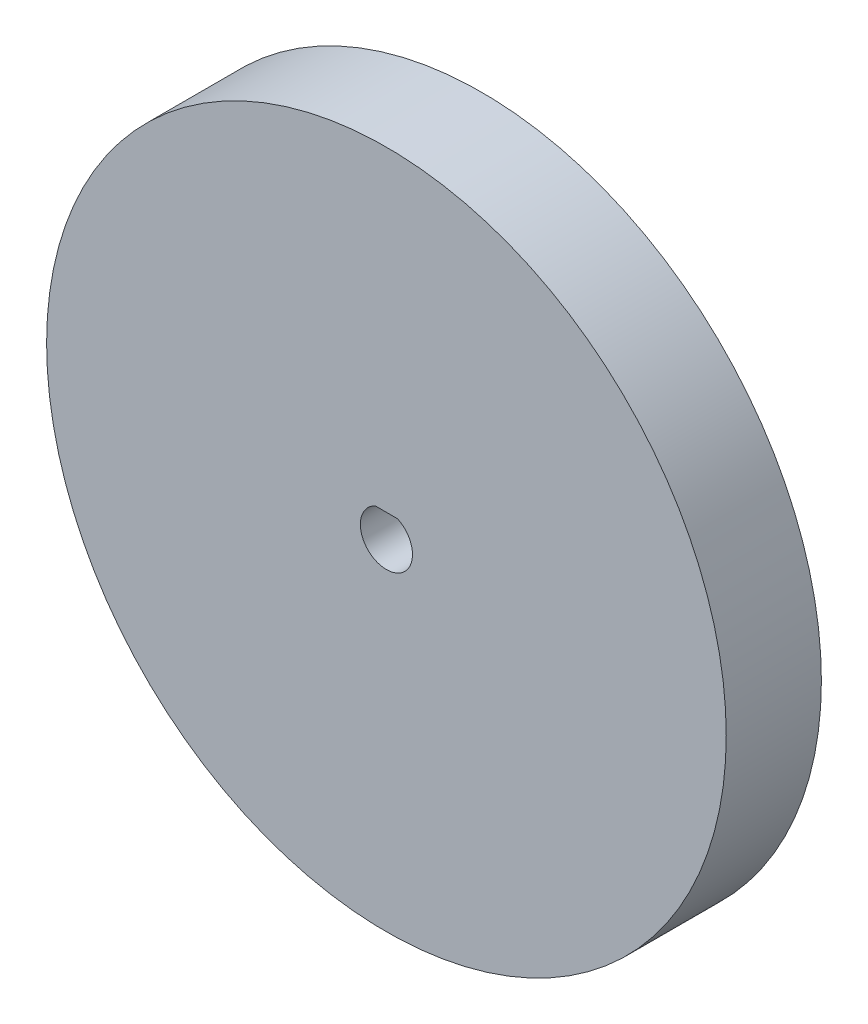
SolidWorks part; units mm, degrees
ref_plane "Front Plane" through (0, 0, 0) normal (0, 0, 1) x (1, 0, 0)
ref_plane "Top Plane" through (0, 0, 0) normal (0, 1, 0) x (1, 0, 0)
ref_plane "Right Plane" through (0, 0, 0) normal (1, 0, 0) x (0, 0, -1)
sketch "Sketch1" plane through (0, 0, 0) normal (0, 0, 1) x (1, 0, 0)
  circle A0 centre (0, 0) radius 38.1
extrude "Boss-Extrude1" add sketch "Sketch1" along normal mid plane 10.668
sketch "Sketch2" plane through (0, 0, -5.334) normal (0, 0, -1) x (-1, 0, 0)
  line L0 (-1.2573, 2.6366) -> (1.2573, 2.6366)
  arc A0 (-1.2573, 2.6366) -> (1.2573, 2.6366) centre (0, 0) ccw
  dimension "D1" = 5.842
  dimension "D2" = 2.5146
extrude "Cut-Extrude1" cut sketch "Sketch2" against normal through all
sketch "Sketch3" plane through (0, 0, -5.334) normal (0, 0, -1) x (-1, 0, 0)
  line L0 (-3.3403, 12.2897) -> (-0.8257, 12.2897)
  dimension "D1" = 2.5146
equation "\"D1@Boss-Extrude1\" = \"WheelLayers@MotorizedPlatform.assembly\"*\"GMaterial@MotorizedPlatform.assembly\""
